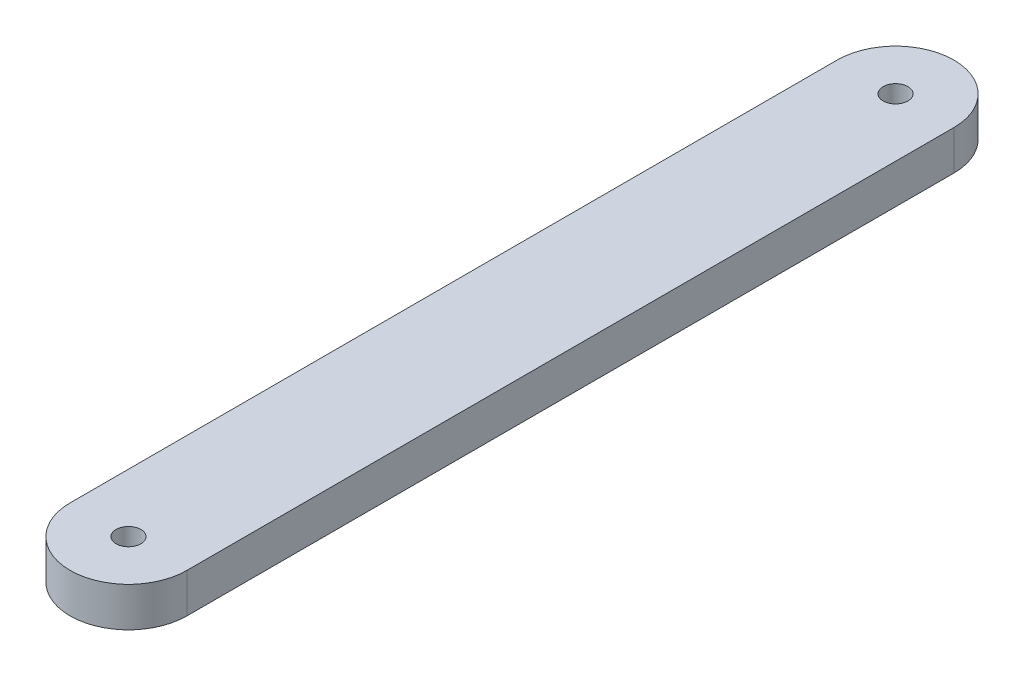
SolidWorks part; units mm, degrees
material "Acrylic (Medium-high impact)"
ref_plane "Front Plane" through (0, 0, 0) normal (0, 0, 1) x (1, 0, 0)
ref_plane "Top Plane" through (0, 0, 0) normal (0, 1, 0) x (1, 0, 0)
ref_plane "Right Plane" through (0, 0, 0) normal (1, 0, 0) x (0, 0, -1)
sketch "Sketch1" plane through (0, 0, 0) normal (0, 1, 0) x (1, 0, 0)
  line L0 (0, -61.722) -> (0, 61.722) construction
  line L1 (-9.4032, -61.722) -> (-9.4032, 61.722)
  line L2 (9.4032, -61.722) -> (9.4032, 61.722)
  arc A0 (-9.4032, -61.722) -> (9.4032, -61.722) centre (0, -61.722) ccw
  arc A1 (9.4032, 61.722) -> (-9.4032, 61.722) centre (0, 61.722) ccw
  point P2 (0, 0)
  dimension "D1" = 123.444
  dimension "D2" = 18.8065
extrude "Boss-Extrude1" add sketch "Sketch1" along normal blind 6.35
hole_wizard "Ø4.0 (4) Diameter Hole1" positions "Sketch2" profile "Sketch3" hole size "Ø4.0" standard "ANSI Metric" end condition through all
sketch "Sketch2" plane through (0, 6.35, 0) normal (0, 1, 0) x (1, 0, 0)
  line L2 (0, 61.722) -> (0, -61.722) construction
  point P0 (0, -61.722)
  point P2 (0, 61.722)
  point P31 (0, 0)
  dimension "D1" = 123.444
sketch "Sketch3" plane through (0, 6.35, 61.722) normal (1, 0, 0) x (0, 0, 1)
  line L0 (0, 0) -> (0, 6.35)
  line L1 (0, 6.35) -> (2, 6.35)
  line L2 (2, 6.35) -> (2, 0)
  line L5 (2, 0) -> (0, 0)
  line L11 (0, -6.35) -> (0, 107.95) construction
  dimension "Thru Hole Dia." = 4
  dimension "Thru Hole Depth" = 6.35
